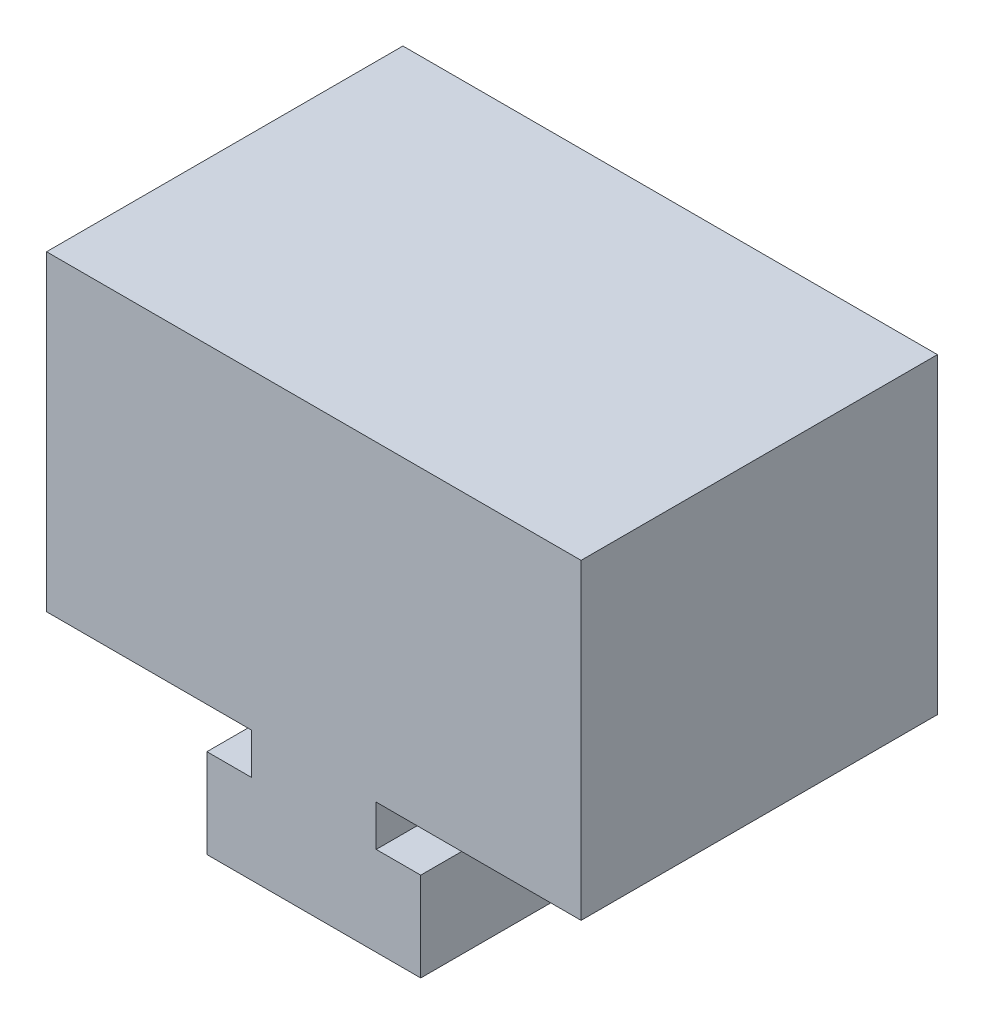
SolidWorks part; units mm, degrees
ref_plane "前视基准面" through (0, 0, 0) normal (0, 0, 1) x (1, 0, 0)
ref_plane "上视基准面" through (0, 0, 0) normal (0, 1, 0) x (1, 0, 0)
ref_plane "右视基准面" through (0, 0, 0) normal (1, 0, 0) x (0, 0, -1)
sketch "草图1" plane through (0, 0, 0) normal (0, 0, 1) x (1, 0, 0)
  line L0 (-6, -16.05) -> (6, -16.05)
  line L2 (-15, -8.75) -> (-15, 8.75)
  line L3 (-15, 8.75) -> (15, 8.75)
  line L4 (15, -8.75) -> (15, 8.75)
  line L5 (-15, -8.75) -> (15, 8.75) construction
  line L6 (-15, 8.75) -> (15, -8.75) construction
  line L7 (-3.5, -8.75) -> (-15, -8.75)
  line L8 (-6, -16.05) -> (-6, -11.05)
  line L9 (3.5, -11.05) -> (3.5, -8.75)
  line L10 (-3.5, -11.05) -> (-3.5, -8.75)
  line L11 (6, -16.05) -> (6, -11.05)
  line L12 (6, -11.05) -> (3.5, -11.05)
  line L13 (-6, -11.05) -> (-3.5, -11.05)
  line L14 (3.5, -8.75) -> (15, -8.75)
  point P0 (0, 0)
  point P12 (0, -12.3)
  point P13 (0, -7.3)
  point P16 (0, -16.05)
  dimension "D1" = 17.5
  dimension "D2" = 30
  dimension "D3" = 2.3
extrude "凸台-拉伸1" add sketch "草图1" along normal blind 20
